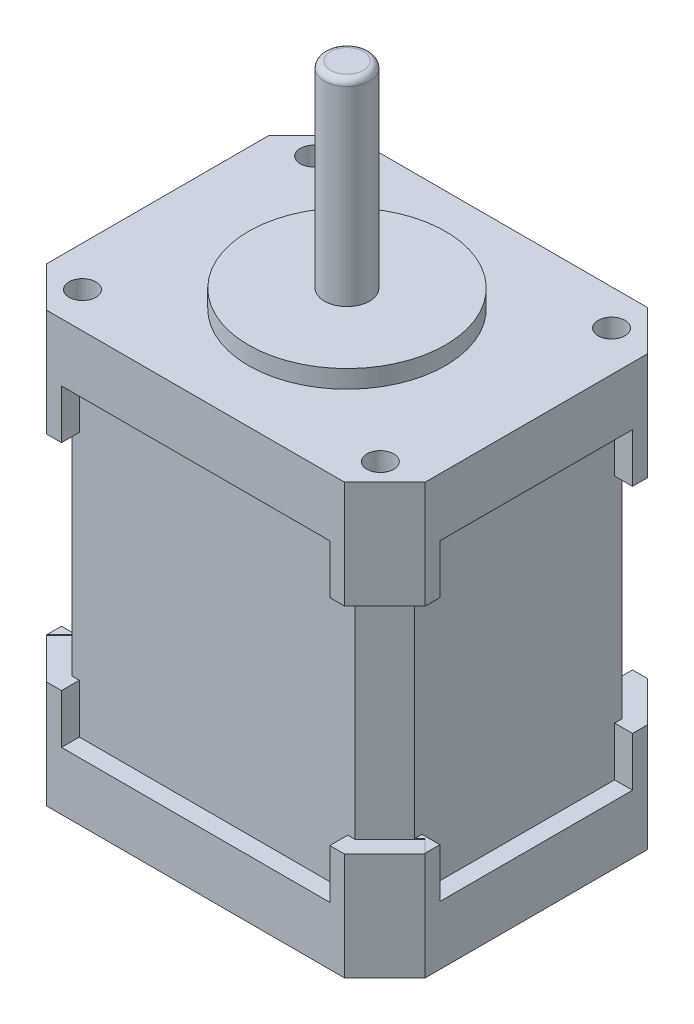
SolidWorks part; units mm, degrees
ref_plane "Front Plane" through (0, 0, 0) normal (0, 0, 1) x (1, 0, 0)
ref_plane "Top Plane" through (0, 0, 0) normal (0, 1, 0) x (1, 0, 0)
ref_plane "Right Plane" through (0, 0, 0) normal (1, 0, 0) x (0, 0, -1)
sketch "Sketch1" plane through (0, 0, 0) normal (0, 1, 0) x (1, 0, 0)
  line L1 (-21.15, -16.92) -> (21.15, -16.92)
  line L2 (-21.15, -16.92) -> (-21.15, 16.92)
  line L3 (-21.15, 16.92) -> (21.15, 16.92)
  line L4 (21.15, -16.92) -> (21.15, 16.92)
  line L5 (-21.15, -16.92) -> (21.15, 16.92) construction
  line L6 (-21.15, 16.92) -> (21.15, -16.92) construction
  point P0 (0, 0)
  dimension "D1" = 42.3
  dimension "D2" = 33.84
extrude "Boss-Extrude1" add sketch "Sketch1" along normal blind 48
sketch "Sketch2" plane through (0, 48, 0) normal (0, 1, 0) x (1, 0, 0)
  circle A0 centre (0, 0) radius 11.0097
extrude "Boss-Extrude2" add sketch "Sketch2" along normal blind 2
chamfer "Chamfer1" distance 4.5 angle 45 1 edges at (21.15, 24, 16.92)
chamfer "Chamfer2" distance 4.5 angle 45 1 edges at (-21.15, 24, 16.92)
chamfer "Chamfer3" distance 4.5 angle 45 1 edges at (21.15, 24, -16.92)
chamfer "Chamfer4" distance 4.5 angle 45 1 edges at (-21.15, 24, -16.92)
sketch "Sketch3" plane through (0, 50, 0) normal (0, 1, 0) x (1, 0, 0)
  circle A0 centre (0, 0) radius 2.5235
extrude "Boss-Extrude3" add sketch "Sketch3" along normal blind 22
sketch "Sketch4" plane through (0, 48, 0) normal (0, 1, 0) x (1, 0, 0)
  line L0 (-18.9, -14.67) -> (0, 0) construction
  line L2 (-21.15, -12.42) -> (-16.65, -16.92) construction
  line L4 (0, 0) -> (18.9, 14.67) construction
  line L6 (0, 0) -> (18.9, -14.67) construction
  line L7 (16.65, -16.92) -> (21.15, -12.42) construction
  line L8 (21.15, 12.42) -> (16.65, 16.92) construction
  line L9 (0, 0) -> (-18.9, 14.67) construction
  line L10 (-16.65, 16.92) -> (-21.15, 12.42) construction
  circle A0 centre (-16.65, -12.9236) radius 1.5
  circle A1 centre (-16.65, 12.9236) radius 1.5
  circle A2 centre (16.65, 12.9236) radius 1.5
  circle A3 centre (16.65, -12.9236) radius 1.5
  dimension "D1" = 3
  dimension "D2" = 3
  dimension "D3" = 3
  dimension "D4" = 3
extrude "Cut-Extrude1" cut sketch "Sketch4" against normal blind 4.5
fillet "Fillet4" radius 0.7 1 edges at (0, 72, 2.5235)
sketch "Sketch5" plane through (0, 0, 16.92) normal (0, 0, 1) x (1, 0, 0)
  line L0 (-16.65, 24) -> (0, 24) construction
  line L1 (-16.65, 48) -> (-16.65, 0) construction
  line L2 (0, 48) -> (0, 24) construction
  line L3 (-16.65, 48) -> (16.65, 48) construction
  line L4 (-15, 6.5) -> (15, 6.5)
  line L5 (0, 0) -> (0, 24) construction
  line L6 (0, 24) -> (16.65, 24) construction
  line L7 (16.65, 0) -> (16.65, 48) construction
  line L8 (-15, 6.5) -> (-15, 41.5)
  line L9 (0, 48) -> (0, 0) construction
  line L10 (-15, 41.5) -> (15, 41.5)
  line L11 (15, 6.5) -> (15, 41.5)
  line L12 (-15, 6.5) -> (15, 41.5) construction
  line L13 (-15, 41.5) -> (15, 6.5) construction
  line L14 (0, 24) -> (0, 36) construction
  line L15 (0, 36) -> (-16.65, 36) construction
  line L16 (-16.65, 36) -> (16.65, 36) construction
  line L17 (16.65, 36) -> (0, 36) construction
  line L18 (0, 36) -> (0, 12) construction
  line L19 (0, 12) -> (15, 12) construction
  line L20 (15, 12) -> (-15, 12) construction
  line L22 (-16.65, 36) -> (-15, 36)
  line L23 (-16.65, 36) -> (-16.65, 12)
  line L24 (-16.65, 12) -> (-15, 12)
  line L25 (-15, 36) -> (-15, 12)
  line L26 (-16.65, 36) -> (-15, 12) construction
  line L27 (-16.65, 12) -> (-15, 36) construction
  line L28 (15, 12) -> (16.65, 12)
  line L29 (15, 12) -> (15, 36)
  line L30 (15, 36) -> (16.65, 36)
  line L31 (16.65, 12) -> (16.65, 36)
  line L32 (15, 12) -> (16.65, 36) construction
  line L33 (15, 36) -> (16.65, 12) construction
  point P25 (-15.825, 24)
  point P28 (15.825, 24)
  line M8 (-16.65, 48) -> (-16.65, 0)
  line M10 (16.65, 0) -> (16.65, 48)
  dimension "D1" = 30
  dimension "D2" = 35
extrude "Cut-Extrude2" cut sketch "Sketch5" against normal blind 2 contours L4 L11 L10 L8 | L30 L11 L28 M10 | L24 L8 L22 M8
sketch "Sketch6" plane through (16.785, 0, 16.785) normal (0.7071, 0, 0.7071) x (0.7071, 0, -0.7071)
  line L0 (6.173, 48) -> (6.173, 0) construction
  line L1 (-0.1909, 36) -> (6.173, 36)
  line L2 (-0.1909, 36) -> (-0.1909, 12)
  line L3 (-0.1909, 12) -> (6.173, 12)
  line L4 (6.173, 36) -> (6.173, 12)
  line L5 (-0.1909, 36) -> (6.173, 12) construction
  line L6 (-0.1909, 12) -> (6.173, 36) construction
  point P4 (2.9911, 24)
extrude "Cut-Extrude4" cut sketch "Sketch6" against normal blind 2
sketch "Sketch8" plane through (21.15, 0, 0) normal (1, 0, 0) x (0, 0, -1)
  line L0 (12.42, 0) -> (12.42, 48) construction
  line L1 (-12.42, 36) -> (12.42, 36)
  line L2 (-12.42, 36) -> (-12.42, 12.0834)
  line L3 (-12.42, 12.0834) -> (12.42, 12.0834)
  line L4 (12.42, 36) -> (12.42, 12.0834)
  line L5 (-12.42, 36) -> (12.42, 12.0834) construction
  line L6 (-12.42, 12.0834) -> (12.42, 36) construction
  line L7 (-12.42, 48) -> (12.42, 48) construction
  line L8 (-10.77, 6.5834) -> (10.77, 6.5834)
  line L9 (-10.77, 6.5834) -> (-10.77, 41.5)
  line L10 (-10.77, 41.5) -> (10.77, 41.5)
  line L11 (10.77, 6.5834) -> (10.77, 41.5)
  line L12 (-10.77, 6.5834) -> (10.77, 41.5) construction
  line L13 (-10.77, 41.5) -> (10.77, 6.5834) construction
  line L14 (-12.42, 48) -> (-12.42, 36) construction
  point P4 (0, 24.0417)
  point P8 (0, 24.0417)
  line M13 (12.42, 0) -> (12.42, 48)
  line M16 (-12.42, 36) -> (-12.42, 12)
  dimension "D1" = 6.5
  dimension "D2" = 1.65
extrude "Cut-Extrude5" cut sketch "Sketch8" against normal blind 2 contours L1 L11 L10 L9 | L3 L11 L1 L9 | L8 L11 L3 L9 | L11 L3 L1 M13 | L3 L9 L1 M16
sketch "Sketch9" plane through (16.785, 0, -16.785) normal (0.7071, 0, -0.7071) x (-0.7071, 0, -0.7071)
  line L0 (0.1909, 48) -> (0.1909, 0) construction
  line L1 (-6.173, 36) -> (0.1909, 36)
  line L2 (-6.173, 36) -> (-6.173, 12.0834)
  line L3 (-6.173, 12.0834) -> (0.1909, 12.0834)
  line L4 (0.1909, 36) -> (0.1909, 12.0834)
  line L5 (-6.173, 36) -> (0.1909, 12.0834) construction
  line L6 (-6.173, 12.0834) -> (0.1909, 36) construction
  point P5 (-2.9911, 24.0417)
extrude "Cut-Extrude7" cut sketch "Sketch9" against normal blind 2
sketch "Sketch10" plane through (0, 0, -16.92) normal (0, 0, -1) x (-1, 0, 0)
  line L0 (16.65, 0) -> (16.65, 48) construction
  line L1 (-16.65, 36) -> (16.65, 36)
  line L2 (-16.65, 36) -> (-16.65, 12.0834)
  line L3 (-16.65, 12.0834) -> (16.65, 12.0834)
  line L4 (16.65, 36) -> (16.65, 12.0834)
  line L5 (-16.65, 36) -> (16.65, 12.0834) construction
  line L6 (-16.65, 12.0834) -> (16.65, 36) construction
  point P4 (0, 24.0417)
extrude "Cut-Extrude8" cut sketch "Sketch10" against normal blind 2
sketch "Sketch11" plane through (0, 0, -16.92) normal (0, 0, -1) x (-1, 0, 0)
  line L0 (-16.65, 48) -> (16.65, 48) construction
  line L1 (-15, 6.5) -> (15, 6.5)
  line L2 (-15, 6.5) -> (-15, 41.5)
  line L3 (-15, 41.5) -> (15, 41.5)
  line L4 (15, 6.5) -> (15, 41.5)
  line L5 (-15, 6.5) -> (15, 41.5) construction
  line L6 (-15, 41.5) -> (15, 6.5) construction
  line L7 (-16.65, 0) -> (16.65, 0) construction
  line L9 (16.65, 36) -> (16.65, 48) construction
  line L10 (-16.65, 48) -> (-16.65, 36) construction
  point P4 (0, 24)
  dimension "D1" = 6.5
  dimension "D2" = 6.5
  dimension "D3" = 1.65
  dimension "D4" = 1.65
extrude "Cut-Extrude10" cut sketch "Sketch11" against normal blind 2
sketch "Sketch12" plane through (-16.785, 0, -16.785) normal (-0.7071, 0, -0.7071) x (-0.7071, 0, 0.7071)
  line L0 (6.173, 48) -> (6.173, 0) construction
  line L1 (-0.1909, 36) -> (6.173, 36)
  line L2 (-0.1909, 36) -> (-0.1909, 12.0834)
  line L3 (-0.1909, 12.0834) -> (6.173, 12.0834)
  line L4 (6.173, 36) -> (6.173, 12.0834)
  line L5 (-0.1909, 36) -> (6.173, 12.0834) construction
  line L6 (-0.1909, 12.0834) -> (6.173, 36) construction
  point P5 (2.9911, 24.0417)
extrude "Cut-Extrude11" cut sketch "Sketch12" against normal blind 2
sketch "Sketch13" plane through (-16.785, 0, 16.785) normal (-0.7071, 0, 0.7071) x (0.7071, 0, 0.7071)
  line L0 (-6.173, 0) -> (-6.173, 48) construction
  line L1 (0.1909, 36) -> (-6.173, 36)
  line L2 (0.1909, 36) -> (0.1909, 12)
  line L3 (0.1909, 12) -> (-6.173, 12)
  line L4 (-6.173, 36) -> (-6.173, 12)
  line L5 (0.1909, 36) -> (-6.173, 12) construction
  line L6 (0.1909, 12) -> (-6.173, 36) construction
  point P4 (-2.9911, 24)
extrude "Cut-Extrude12" cut sketch "Sketch13" against normal blind 2
sketch "Sketch14" plane through (-21.15, 0, 0) normal (-1, 0, 0) x (0, 0, 1)
  line L0 (-12.42, 48) -> (12.42, 48) construction
  line L1 (12.42, 36) -> (-12.42, 36)
  line L2 (12.42, 36) -> (12.42, 12.0834)
  line L3 (12.42, 12.0834) -> (-12.42, 12.0834)
  line L4 (-12.42, 36) -> (-12.42, 12.0834)
  line L5 (12.42, 36) -> (-12.42, 12.0834) construction
  line L6 (12.42, 12.0834) -> (-12.42, 36) construction
  line L7 (-10.77, 41.5) -> (10.77, 41.5)
  line L8 (-10.77, 41.5) -> (-10.77, 6.5)
  line L9 (-10.77, 6.5) -> (10.77, 6.5)
  line L10 (10.77, 41.5) -> (10.77, 6.5)
  line L11 (-10.77, 41.5) -> (10.77, 6.5) construction
  line L12 (-10.77, 6.5) -> (10.77, 41.5) construction
  line L13 (-12.42, 0) -> (12.42, 0) construction
  line L14 (-12.42, 48) -> (-12.42, 36) construction
  line L15 (12.42, 36) -> (12.42, 48) construction
  point P4 (0, 24.0417)
  point P11 (0, 24)
  line M7 (-12.42, 36) -> (-12.42, 12.0834)
  line M11 (12.42, 12) -> (12.42, 36)
  dimension "D1" = 6.5
  dimension "D2" = 6.5
  dimension "D3" = 1.65
  dimension "D4" = 1.65
extrude "Cut-Extrude13" cut sketch "Sketch14" against normal blind 2 contours L10 L7 L8 L1 | L10 L1 L8 L3 | L10 L3 L8 L9 | L1 L10 L3 M11 | L8 L1 L3 M7
